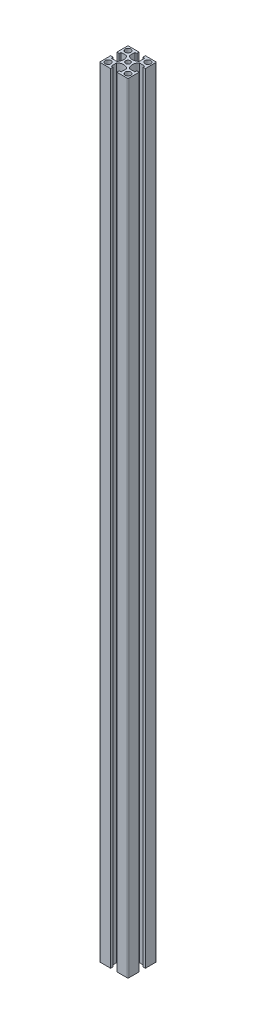
SolidWorks part; units mm, degrees
ref_plane "前基準面" through (0, 0, 0) normal (0, 0, 1) x (1, 0, 0)
ref_plane "上基準面" through (0, 0, 0) normal (0, 1, 0) x (1, 0, 0)
ref_plane "右基準面" through (0, 0, 0) normal (1, 0, 0) x (0, 0, -1)
sketch "草圖1" plane through (0, 0, 0) normal (0, 1, 0) x (1, 0, 0)
  line L0 (0, 0) -> (73.6974, 0) construction
  line L1 (0, 0) -> (0, 61.8032) construction
  line L2 (0, 0) -> (68.0109, 68.0109) construction
  line L3 (5.25, 6.6439) -> (5.25, 12.5)
  line L4 (5.25, 12.5) -> (3.25, 12.5)
  line L5 (3.25, 12.5) -> (3.25, 15)
  line L6 (3.25, 15) -> (15, 15)
  line L7 (15, 3.25) -> (15, 15)
  line L8 (12.5, 3.25) -> (15, 3.25)
  line L9 (12.5, 5.25) -> (12.5, 3.25)
  line L10 (6.6439, 5.25) -> (12.5, 5.25)
  line L11 (-6.6439, 5.25) -> (-12.5, 5.25)
  line L12 (-12.5, 5.25) -> (-12.5, 3.25)
  line L13 (-12.5, 3.25) -> (-15, 3.25)
  line L14 (-15, 3.25) -> (-15, 15)
  line L15 (-3.25, 15) -> (-15, 15)
  line L16 (-3.25, 12.5) -> (-3.25, 15)
  line L17 (-5.25, 12.5) -> (-3.25, 12.5)
  line L18 (-5.25, 6.6439) -> (-5.25, 12.5)
  line L19 (5.25, 6.6439) -> (6.6439, 5.25) construction
  line L20 (5.947, 5.947) -> (15, 15) construction
  line L21 (5.947, -5.947) -> (15, -15) construction
  line L22 (5.25, -6.6439) -> (6.6439, -5.25) construction
  line L23 (-5.25, -6.6439) -> (-5.25, -12.5)
  line L24 (-5.25, -12.5) -> (-3.25, -12.5)
  line L25 (-3.25, -12.5) -> (-3.25, -15)
  line L26 (-3.25, -15) -> (-15, -15)
  line L27 (-15, -3.25) -> (-15, -15)
  line L28 (-12.5, -3.25) -> (-15, -3.25)
  line L29 (-12.5, -5.25) -> (-12.5, -3.25)
  line L30 (-6.6439, -5.25) -> (-12.5, -5.25)
  line L31 (6.6439, -5.25) -> (12.5, -5.25)
  line L32 (12.5, -5.25) -> (12.5, -3.25)
  line L33 (12.5, -3.25) -> (15, -3.25)
  line L34 (15, -3.25) -> (15, -15)
  line L35 (3.25, -15) -> (15, -15)
  line L36 (3.25, -12.5) -> (3.25, -15)
  line L37 (5.25, -12.5) -> (3.25, -12.5)
  line L38 (5.25, -6.6439) -> (5.25, -12.5)
  circle A0 centre (0, 0) radius 2.5
  arc A1 (-5.25, 6.6439) -> (5.25, 6.6439) centre (0, 12) ccw
  arc A2 (6.6439, -5.25) -> (6.6439, 5.25) centre (12, 0) cw
  arc A3 (-6.6439, -5.25) -> (-6.6439, 5.25) centre (-12, 0) ccw
  circle A4 centre (10.4735, 10.4735) radius 3
  circle A5 centre (-10.4735, 10.4735) radius 3
  circle A6 centre (-10.4735, -10.4735) radius 3
  circle A7 centre (10.4735, -10.4735) radius 3
  arc A8 (-5.25, -6.6439) -> (5.25, -6.6439) centre (0, -12) cw
  dimension "D2" = 7.5
  dimension "D3" = 10.5
  dimension "D6" = 5
  dimension "D7" = 10.5
  dimension "D9" = 6
  dimension "D4" = 6.5
  dimension "D5" = 30
  dimension "D8" = 2.5
extrude "填料-伸長1" add sketch "草圖1" along normal blind 820
fillet "圓角1" radius 1 4 edges at (-15, 410, -15) (15, 410, -15) (-15, 410, 15) (15, 410, 15)
